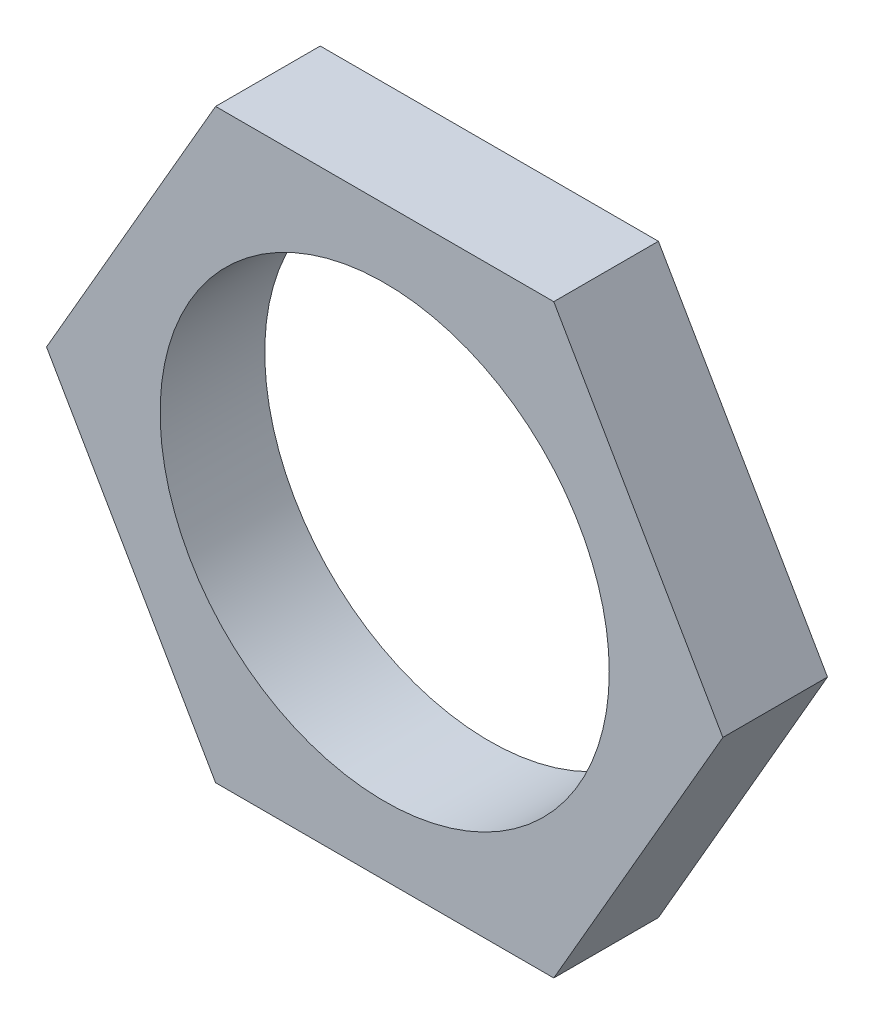
SolidWorks part; units mm, degrees
material "Plain Carbon Steel"
ref_plane "Front Plane" through (0, 0, 0) normal (0, 0, 1) x (1, 0, 0)
ref_plane "Top Plane" through (0, 0, 0) normal (0, 1, 0) x (1, 0, 0)
ref_plane "Right Plane" through (0, 0, 0) normal (1, 0, 0) x (0, 0, -1)
sketch "Sketch1" plane through (0, 0, 0) normal (0, 0, 1) x (1, 0, 0)
  line L1 (4.9053, 8.4963) -> (-4.9053, 8.4963)
  line L2 (-4.9053, 8.4963) -> (-9.8107, 0)
  line L3 (-9.8107, 0) -> (-4.9053, -8.4963)
  line L4 (-4.9053, -8.4963) -> (4.9053, -8.4963)
  line L5 (4.9053, -8.4963) -> (9.8107, 0)
  line L6 (9.8107, 0) -> (4.9053, 8.4963)
  circle A0 centre (0, 0) radius 8.4963 construction
  circle A1 centre (0, 0) radius 6.5151
  dimension "D2" = 13.0302
  dimension "D1" = 16.9926
extrude "Boss-Extrude1" add sketch "Sketch1" along normal blind 3.0353
